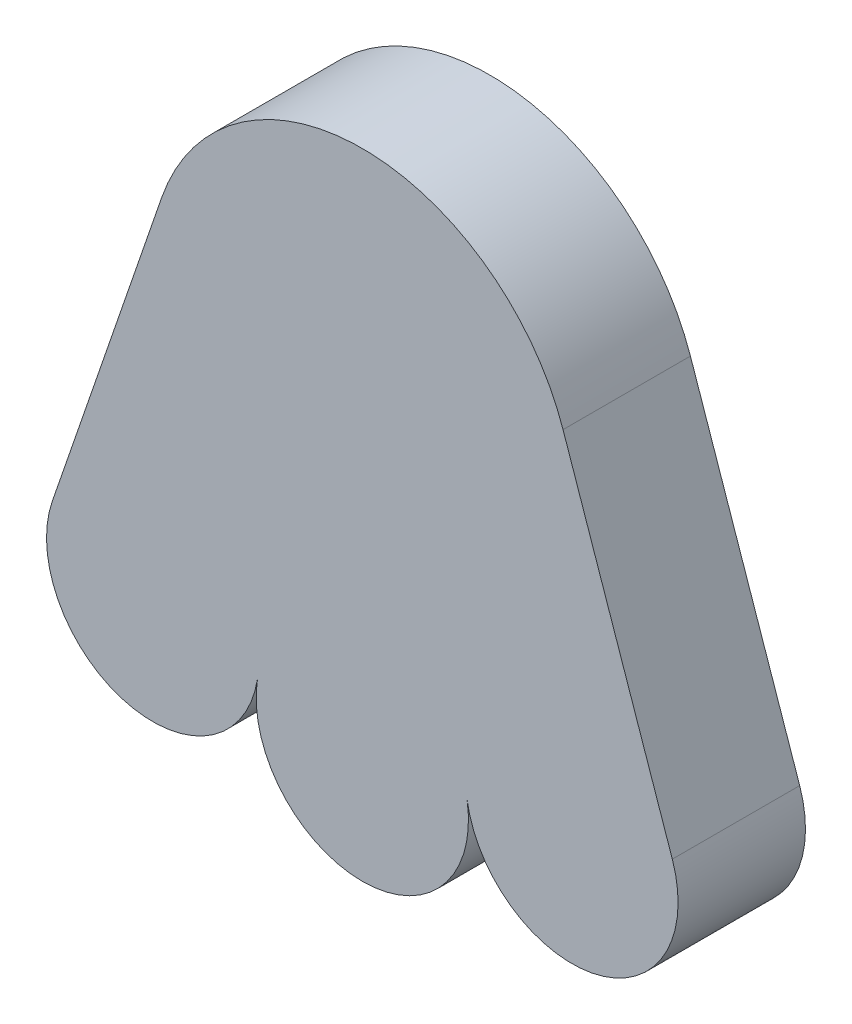
SolidWorks part; units mm, degrees
ref_plane "Alzado" through (0, 0, 0) normal (0, 0, 1) x (1, 0, 0)
ref_plane "Planta" through (0, 0, 0) normal (0, 1, 0) x (1, 0, 0)
ref_plane "Vista lateral" through (0, 0, 0) normal (1, 0, 0) x (0, 0, -1)
sketch "Croquis1" plane through (0, 0, 0) normal (0, 0, 1) x (1, 0, 0)
  line L1 (-4.7276, 4.6278) -> (-7.3011, -2.8463)
  line L2 (4.7276, 4.6278) -> (7.3011, -2.8463)
  arc A0 (-7.3011, -2.8463) -> (-2.4687, -4.0547) centre (-4.9373, -3.6602) ccw
  arc A1 (7.3011, -2.8463) -> (2.4687, -4.0547) centre (4.9373, -3.6602) cw
  arc A2 (-2.4687, -4.0547) -> (2.4687, -4.0547) centre (0, -4.4493) ccw
  arc A3 (4.7276, 4.6278) -> (-4.7276, 4.6278) centre (0, 3) ccw
  point P0 (0, 0)
  point P3 (0, 0)
  point P4 (0, 0)
  dimension "D3" = 5
  dimension "D5" = 5
  dimension "D6" = 10
extrude "Saliente-Extruir1" add sketch "Croquis1" along normal blind 3
